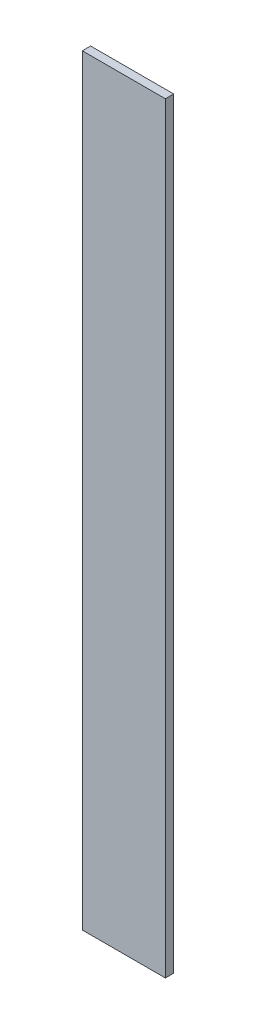
SolidWorks part; units mm, degrees
material "Balsa"
ref_plane "Front Plane" through (0, 0, 0) normal (1, 0, 0) x (0, 1, 0)
ref_plane "Top Plane" through (0, 0, 0) normal (0, 0, 1) x (0, 1, 0)
ref_plane "Right Plane" through (0, 0, 0) normal (0, 1, 0) x (-1, 0, 0)
sketch "Sketch1" plane through (0, 0, 0) normal (0, 0, 1) x (0, 1, 0)
  line L1 (-137.5, -15) -> (137.5, -15)
  line L2 (-137.5, -15) -> (-137.5, 15)
  line L3 (-137.5, 15) -> (137.5, 15)
  line L4 (137.5, -15) -> (137.5, 15)
  line L5 (-137.5, -15) -> (137.5, 15) construction
  line L6 (-137.5, 15) -> (137.5, -15) construction
  point P0 (0, 0)
  dimension "D1" = 275
  dimension "D2" = 30
extrude "Boss-Extrude1" add sketch "Sketch1" along normal blind 3
sketch "Sketch2" plane through (0, 0, 0) normal (0, 0, -1) x (1, 0, 0)
  line L4 (5.6908, -115.5) -> (5.6908, -112)
  line L5 (5.6908, -112) -> (-2.8092, -112)
  line L6 (-2.8092, -115.5) -> (5.6908, -115.5)
  line L7 (-2.8092, -112) -> (-2.8092, -115.5)
  line L16 (-2.8092, -55) -> (-2.8092, -58.5)
  line L17 (-2.8092, -58.5) -> (5.6908, -58.5)
  line L18 (5.6908, -55) -> (-2.8092, -55)
  line L19 (5.6908, -58.5) -> (5.6908, -55)
  line L20 (5.6908, -88.5) -> (-2.8092, -88.5)
  line L21 (-2.8092, -88.5) -> (-2.8092, -92)
  line L22 (-2.8092, -92) -> (5.6908, -92)
  line L23 (5.6908, -92) -> (5.6908, -88.5)
  spline S2 degree 3 poles (2.0604, -31.8082) (1.4408, -31.7216) (0.8212, -31.8082) (0.2174, -32.0692) (-0.3637, -32.4957) (-0.9247, -33.0825) (-1.4674, -33.8277) (-1.9925, -34.7303) (-2.4993, -35.7889) (-2.9867, -37.0016) (-3.4532, -38.3661) (-3.8973, -39.8794) (-4.3173, -41.5382) (-4.7116, -43.3387) (-5.0788, -45.2768) (-5.4173, -47.3481) (-5.7258, -49.5478) (-6.0034, -51.8707) (-6.2489, -54.3115) (-6.4617, -56.8644) (-6.6414, -59.5236) (-6.7876, -62.2828) (-6.9003, -65.1355) (-6.9798, -68.0752) (-7.0264, -71.0949) (-7.041, -74.1876) (-7.0244, -77.3462) (-6.9777, -80.5631) (-6.9021, -83.8309) (-6.799, -87.142) (-6.6701, -90.4887) (-6.5169, -93.8631) (-6.3412, -97.2573) (-6.1447, -100.6635) (-5.9293, -104.0736) (-5.6969, -107.4798) (-5.4491, -110.874) (-5.188, -114.2483) (-4.9152, -117.5949) (-4.6325, -120.9059) (-4.3416, -124.1737) (-4.0442, -127.3905) (-3.7421, -130.5488) (-3.4366, -133.6414) (-3.1294, -136.6609) (-2.8221, -139.6003) (-2.516, -142.4528) (-2.2127, -145.2116) (-1.9136, -147.8704) (-1.6201, -150.4229) (-1.3337, -152.8631) (-1.0558, -155.1855) (-0.7876, -157.3845) (-0.5307, -159.4549) (-0.2862, -161.3921) (-0.0557, -163.1914) (0.1598, -164.8486) (0.3589, -166.3599) (0.5405, -167.7218) (0.7036, -168.931) (0.8468, -169.9849) (0.9704, -170.8804) (1.0705, -171.6171) (1.1546, -172.1891) (1.2023, -172.6048) (1.2539, -172.8436) (1.2493, -173.0886) (1.6322, -173.0886) (1.6276, -172.8436) (1.6792, -172.6048) (1.7269, -172.1891) (1.811, -171.6171) (1.9111, -170.8804) (2.0347, -169.9849) (2.178, -168.931) (2.341, -167.7218) (2.5227, -166.3599) (2.7218, -164.8486) (2.9372, -163.1914) (3.1678, -161.3921) (3.4122, -159.4549) (3.6691, -157.3845) (3.9373, -155.1855) (4.2153, -152.8631) (4.5017, -150.4229) (4.7951, -147.8704) (5.0942, -145.2116) (5.3975, -142.4528) (5.7036, -139.6003) (6.011, -136.6609) (6.3181, -133.6414) (6.6236, -130.5488) (6.9258, -127.3905) (7.2231, -124.1737) (7.514, -120.9059) (7.7967, -117.5949) (8.0695, -114.2483) (8.3306, -110.874) (8.5784, -107.4798) (8.8109, -104.0736) (9.0262, -100.6635) (9.2227, -97.2573) (9.3984, -93.8631) (9.5516, -90.4887) (9.6806, -87.142) (9.7836, -83.8309) (9.8592, -80.5631) (9.9059, -77.3462) (9.9225, -74.1876) (9.908, -71.0949) (9.8613, -68.0752) (9.7818, -65.1355) (9.6691, -62.2828) (9.5229, -59.5236) (9.3432, -56.8644) (9.1304, -54.3115) (8.8849, -51.8707) (8.6073, -49.5478) (8.2988, -47.3481) (7.9603, -45.2768) (7.5932, -43.3387) (7.1988, -41.5382) (6.7788, -39.8794) (6.3347, -38.3661) (5.8682, -37.0016) (5.3808, -35.7889) (4.874, -34.7303) (4.3489, -33.8277) (3.8062, -33.0825) (3.2452, -32.4957) (2.6641, -32.0692) (2.0604, -31.8082) (1.4408, -31.7216) (0.8212, -31.8082) knots -0.006773 -0.004321 -0.002106 0 0.002106 0.004321 0.006773 0.009557 0.012734 0.016343 0.020406 0.024934 0.029933 0.035402 0.041337 0.047732 0.054575 0.061857 0.069565 0.077682 0.086195 0.095084 0.104333 0.113922 0.123829 0.134035 0.144516 0.155249 0.16621 0.177376 0.18872 0.200217 0.21184 0.223563 0.235359 0.2472 0.259058 0.270907 0.282718 0.294465 0.306118 0.317651 0.329037 0.340249 0.35126 0.362045 0.372579 0.382836 0.392793 0.402425 0.411711 0.420628 0.429156 0.437273 0.444962 0.452203 0.458979 0.465275 0.471075 0.476366 0.481134 0.485369 0.48906 0.492198 0.494776 0.496788 0.498228 0.499094 0.499383 0.500617 0.500906 0.501772 0.503212 0.505224 0.507802 0.51094 0.514631 0.518866 0.523634 0.528925 0.534725 0.541021 0.547797 0.555038 0.562727 0.570844 0.579372 0.588289 0.597575 0.607207 0.617164 0.627421 0.637955 0.64874 0.659751 0.670963 0.682349 0.693882 0.705535 0.717282 0.729093 0.740942 0.7528 0.764641 0.776437 0.78816 0.799783 0.81128 0.822624 0.83379 0.844751 0.855484 0.865965 0.876171 0.886078 0.895667 0.904916 0.913805 0.922318 0.930435 0.938143 0.945425 0.952268 0.958663 0.964598 0.970067 0.975066 0.979594 0.983657 0.987266 0.990443 0.993227 0.995679 0.997894 1 1.002106 1.004321 1.006773 only from (1.4408, -31.75) to (1.4408, -31.75)
  spline S4 degree 3 poles (2.0604, -31.8082) (1.4408, -31.7216) (0.8212, -31.8082) (0.2174, -32.0692) (-0.3637, -32.4957) (-0.9247, -33.0825) (-1.4674, -33.8277) (-1.9925, -34.7303) (-2.4993, -35.7889) (-2.9867, -37.0016) (-3.4532, -38.3661) (-3.8973, -39.8794) (-4.3173, -41.5382) (-4.7116, -43.3387) (-5.0788, -45.2768) (-5.4173, -47.3481) (-5.7258, -49.5478) (-6.0034, -51.8707) (-6.2489, -54.3115) (-6.4617, -56.8644) (-6.6414, -59.5236) (-6.7876, -62.2828) (-6.9003, -65.1355) (-6.9798, -68.0752) (-7.0264, -71.0949) (-7.041, -74.1876) (-7.0244, -77.3462) (-6.9777, -80.5631) (-6.9021, -83.8309) (-6.799, -87.142) (-6.6701, -90.4887) (-6.5169, -93.8631) (-6.3412, -97.2573) (-6.1447, -100.6635) (-5.9293, -104.0736) (-5.6969, -107.4798) (-5.4491, -110.874) (-5.188, -114.2483) (-4.9152, -117.5949) (-4.6325, -120.9059) (-4.3416, -124.1737) (-4.0442, -127.3905) (-3.7421, -130.5488) (-3.4366, -133.6414) (-3.1294, -136.6609) (-2.8221, -139.6003) (-2.516, -142.4528) (-2.2127, -145.2116) (-1.9136, -147.8704) (-1.6201, -150.4229) (-1.3337, -152.8631) (-1.0558, -155.1855) (-0.7876, -157.3845) (-0.5307, -159.4549) (-0.2862, -161.3921) (-0.0557, -163.1914) (0.1598, -164.8486) (0.3589, -166.3599) (0.5405, -167.7218) (0.7036, -168.931) (0.8468, -169.9849) (0.9704, -170.8804) (1.0705, -171.6171) (1.1546, -172.1891) (1.2023, -172.6048) (1.2539, -172.8436) (1.2493, -173.0886) (1.6322, -173.0886) (1.6276, -172.8436) (1.6792, -172.6048) (1.7269, -172.1891) (1.811, -171.6171) (1.9111, -170.8804) (2.0347, -169.9849) (2.178, -168.931) (2.341, -167.7218) (2.5227, -166.3599) (2.7218, -164.8486) (2.9372, -163.1914) (3.1678, -161.3921) (3.4122, -159.4549) (3.6691, -157.3845) (3.9373, -155.1855) (4.2153, -152.8631) (4.5017, -150.4229) (4.7951, -147.8704) (5.0942, -145.2116) (5.3975, -142.4528) (5.7036, -139.6003) (6.011, -136.6609) (6.3181, -133.6414) (6.6236, -130.5488) (6.9258, -127.3905) (7.2231, -124.1737) (7.514, -120.9059) (7.7967, -117.5949) (8.0695, -114.2483) (8.3306, -110.874) (8.5784, -107.4798) (8.8109, -104.0736) (9.0262, -100.6635) (9.2227, -97.2573) (9.3984, -93.8631) (9.5516, -90.4887) (9.6806, -87.142) (9.7836, -83.8309) (9.8592, -80.5631) (9.9059, -77.3462) (9.9225, -74.1876) (9.908, -71.0949) (9.8613, -68.0752) (9.7818, -65.1355) (9.6691, -62.2828) (9.5229, -59.5236) (9.3432, -56.8644) (9.1304, -54.3115) (8.8849, -51.8707) (8.6073, -49.5478) (8.2988, -47.3481) (7.9603, -45.2768) (7.5932, -43.3387) (7.1988, -41.5382) (6.7788, -39.8794) (6.3347, -38.3661) (5.8682, -37.0016) (5.3808, -35.7889) (4.874, -34.7303) (4.3489, -33.8277) (3.8062, -33.0825) (3.2452, -32.4957) (2.6641, -32.0692) (2.0604, -31.8082) (1.4408, -31.7216) (0.8212, -31.8082) knots -0.006773 -0.004321 -0.002106 0 0.002106 0.004321 0.006773 0.009557 0.012734 0.016343 0.020406 0.024934 0.029933 0.035402 0.041337 0.047732 0.054575 0.061857 0.069565 0.077682 0.086195 0.095084 0.104333 0.113922 0.123829 0.134035 0.144516 0.155249 0.16621 0.177376 0.18872 0.200217 0.21184 0.223563 0.235359 0.2472 0.259058 0.270907 0.282718 0.294465 0.306118 0.317651 0.329037 0.340249 0.35126 0.362045 0.372579 0.382836 0.392793 0.402425 0.411711 0.420628 0.429156 0.437273 0.444962 0.452203 0.458979 0.465275 0.471075 0.476366 0.481134 0.485369 0.48906 0.492198 0.494776 0.496788 0.498228 0.499094 0.499383 0.500617 0.500906 0.501772 0.503212 0.505224 0.507802 0.51094 0.514631 0.518866 0.523634 0.528925 0.534725 0.541021 0.547797 0.555038 0.562727 0.570844 0.579372 0.588289 0.597575 0.607207 0.617164 0.627421 0.637955 0.64874 0.659751 0.670963 0.682349 0.693882 0.705535 0.717282 0.729093 0.740942 0.7528 0.764641 0.776437 0.78816 0.799783 0.81128 0.822624 0.83379 0.844751 0.855484 0.865965 0.876171 0.886078 0.895667 0.904916 0.913805 0.922318 0.930435 0.938143 0.945425 0.952268 0.958663 0.964598 0.970067 0.975066 0.979594 0.983657 0.987266 0.990443 0.993227 0.995679 0.997894 1 1.002106 1.004321 1.006773 only from (1.4408, -31.75) to (1.4408, -31.75)
